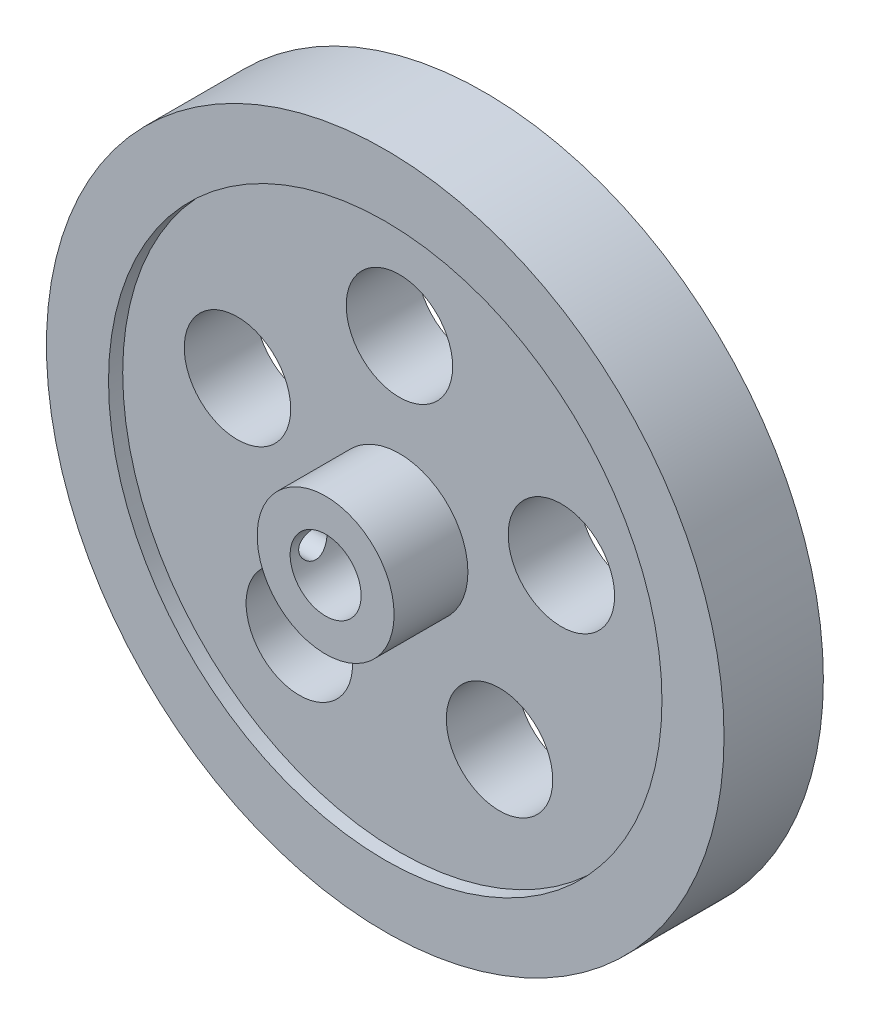
SolidWorks part; units mm, degrees
ref_plane "前视基准面" through (0, 0, 0) normal (0, 0, 1) x (1, 0, 0)
ref_plane "上视基准面" through (0, 0, 0) normal (0, 1, 0) x (1, 0, 0)
ref_plane "右视基准面" through (0, 0, 0) normal (1, 0, 0) x (0, 0, -1)
sketch "草图1" plane through (0, 0, 0) normal (0, 0, 1) x (1, 0, 0)
  circle A0 centre (0, 0) radius 47.75
  dimension "D1" = 95.5
extrude "凸台-拉伸1" add sketch "草图1" along normal blind 14
sketch "草图2" plane through (0, 0, 14) normal (0, 0, 1) x (1, 0, 0)
  circle A0 centre (0, 0) radius 9.65
  dimension "D1" = 19.3
extrude "凸台-拉伸2" add sketch "草图2" along normal blind 8.4
sketch "草图3" plane through (0, 0, 22.4) normal (0, 0, 1) x (1, 0, 0)
  circle A0 centre (0, 0) radius 5
  dimension "D1" = 10
extrude "切除-拉伸1" cut sketch "草图3" against normal up to surface (22.4 mm away) up to face at (47.75, 0, 0)
sketch "草图6" plane through (0, 0, 0) normal (1, 0, 0) x (0, 0, -1)
  line L0 (-22.4, 9.65) -> (-22.4, -9.65) construction
  line L1 (-22.4, 0) -> (0, 0) construction
  circle A0 centre (-19.2, 0) radius 2
  point P7 (-19.2, 0)
  dimension "D1" = 4
  dimension "D2" = 3.2
extrude "切除-拉伸2" cut sketch "草图6" against normal up to next
sketch "草图7" plane through (0, 0, 14) normal (0, 0, 1) x (1, 0, 0)
  circle A0 centre (0, 0) radius 39
  circle A1 centre (0, 0) radius 9.65 construction
  circle A2 centre (0, 0) radius 9.65
  dimension "D1" = 78
extrude "切除-拉伸3" cut sketch "草图7" against normal blind 2
sketch "草图8" plane through (0, 0, 0) normal (0, 0, -1) x (-1, 0, 0)
  circle A0 centre (0, 0) radius 39 construction
  circle A1 centre (0, 0) radius 39
  circle A2 centre (0, 0) radius 9.65 construction
  circle A3 centre (0, 0) radius 9.65
extrude "切除-拉伸4" cut sketch "草图8" against normal blind 2
sketch "草图9" plane through (0, 0, 12) normal (0, 0, 1) x (1, 0, 0)
  line L0 (0, 0) -> (0, 52.4568) construction
  circle A0 centre (0, 24) radius 7.5
  circle A1 centre (22.8254, 7.4164) radius 7.5
  circle A2 centre (14.1068, -19.4164) radius 7.5
  circle A3 centre (-14.1068, -19.4164) radius 7.5
  circle A4 centre (-22.8254, 7.4164) radius 7.5
  point P16 (0, 0)
  dimension "D2" = 15
  dimension "D1" = 24
  dimension "D3" = 5
extrude "切除-拉伸5" cut sketch "草图9" against normal up to next
